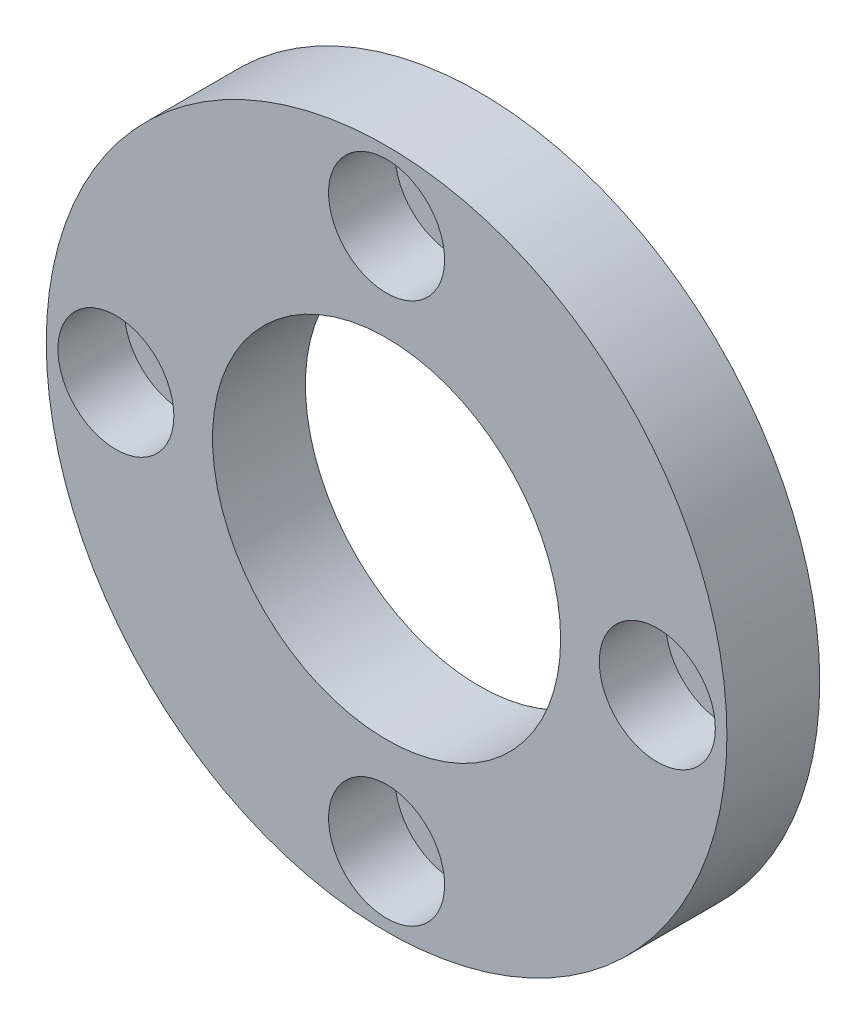
SolidWorks part; units mm, degrees
ref_plane "Ön Düzlem" through (0, 0, 0) normal (0, 0, 1) x (1, 0, 0)
ref_plane "Üst Düzlem" through (0, 0, 0) normal (0, 1, 0) x (1, 0, 0)
ref_plane "Sağ Düzlem" through (0, 0, 0) normal (1, 0, 0) x (0, 0, -1)
sketch "Çizim1" plane through (0, 0, 0) normal (0, 0, 1) x (1, 0, 0)
  circle A0 centre (0, 0) radius 44
  circle A1 centre (0, 0) radius 22.5
  dimension "D1" = 88
  dimension "D2" = 45
extrude "Yükseklik-Ekstrüzyon1" add sketch "Çizim1" along normal blind 12
hole_wizard "M8 Altıgen Alyan Başlı Kör Vida İçin Havşa1" positions "Çizim4" profile "Çizim5" size "M8" standard "ISO" slot yes
sketch "Çizim4" plane through (0, 0, 12) normal (0, 0, 1) x (1, 0, 0)
  line L0 (0, 0) -> (35, 0) construction
  line L2 (0, 0) -> (0, -35) construction
  line L4 (0, 0) -> (-35, 0) construction
  line L6 (0, 0) -> (0, 35) construction
  point P0 (0, -35)
  point P3 (-35, 0)
  point P6 (0, 35)
  point P9 (35, 0)
  dimension "D1" = 35
  dimension "D2" = 35
  dimension "D3" = 35
  dimension "D4" = 35
sketch "Çizim5" plane through (0, -35, 12) normal (1, 0, 0) x (0, -1, 0)
  line L0 (0, 0) -> (0, 24.9539)
  line L1 (0, 24.9539) -> (4.5, 22.25)
  line L2 (4.5, 22.25) -> (4.5, 8.6)
  line L3 (4.5, 8.6) -> (7.5, 8.6)
  line L4 (7.5, 8.6) -> (7.5, 0)
  line L5 (7.5, 0) -> (0, 0)
  line L10 (0, 24.9539) -> (-4.5, 22.25) construction
  line L11 (0, -6.35) -> (0, 107.95) construction
  dimension "Hole Dia." = 9
  dimension "Hole Depth" = 22.25
  dimension "C'Bore Dia." = 15
  dimension "C'Bore Depth" = 8.6
  dimension "Drill Angle" = 118
